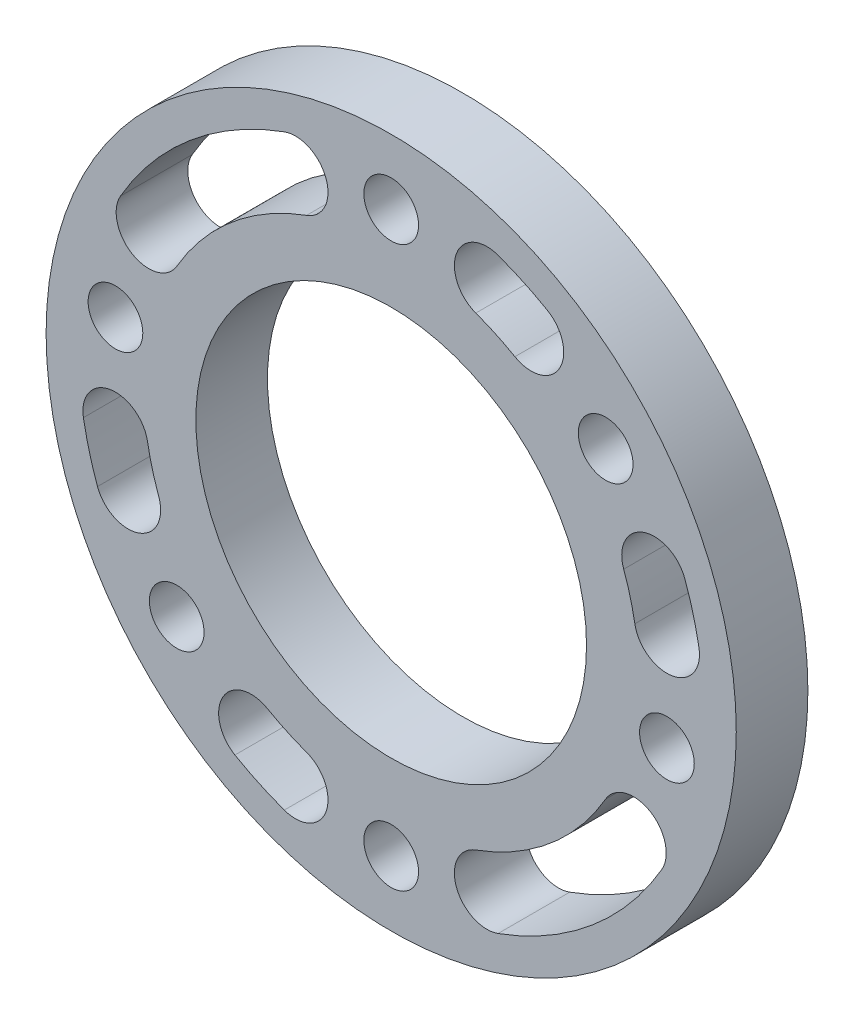
SolidWorks part; units mm, degrees
material "6061 合金"
ref_plane "前视基准面" through (0, 0, 0) normal (0, 0, 1) x (1, 0, 0)
ref_plane "上视基准面" through (0, 0, 0) normal (0, 1, 0) x (1, 0, 0)
ref_plane "右视基准面" through (0, 0, 0) normal (1, 0, 0) x (0, 0, -1)
sketch "草图1" plane through (0, 0, 0) normal (0, 0, 1) x (1, 0, 0)
  circle A0 centre (0, 0) radius 15
  circle A1 centre (0, 0) radius 26.5
  circle A2 centre (0, 0) radius 21.5 construction
  circle A3 centre (0, 21.5) radius 2.1
  circle A4 centre (16.47, 13.8199) radius 2.1
  circle A5 centre (21.1734, -3.7334) radius 2.1
  circle A6 centre (0, -21.5) radius 2.1
  circle A7 centre (-16.47, -13.8199) radius 2.1
  circle A8 centre (-21.1734, 3.7334) radius 2.1
  arc A9 (-18.6195, 10.75) -> (-7.3534, 20.2034) centre (0, 0) cw construction
  arc A10 (-8.2085, 22.5526) -> (-20.7846, 12) centre (0, 0) ccw
  arc A11 (-6.4984, 17.8542) -> (-16.4545, 9.5) centre (0, 0) ccw
  arc A12 (-6.4984, 17.8542) -> (-8.2085, 22.5526) centre (-7.3534, 20.2034) ccw
  arc A13 (-20.7846, 12) -> (-16.4545, 9.5) centre (-18.6195, 10.75) ccw
  arc A14 (7.3534, 20.2034) -> (10.75, 18.6195) centre (0, 0) cw construction
  arc A15 (12, 20.7846) -> (8.2085, 22.5526) centre (0, 0) ccw
  arc A16 (9.5, 16.4545) -> (6.4984, 17.8542) centre (0, 0) ccw
  arc A17 (9.5, 16.4545) -> (12, 20.7846) centre (10.75, 18.6195) ccw
  arc A18 (8.2085, 22.5526) -> (6.4984, 17.8542) centre (7.3534, 20.2034) ccw
  arc A19 (18.7113, 3.2993) -> (17.8542, 6.4984) centre (0, 0) ccw
  arc A20 (18.7113, 3.2993) -> (23.6354, 4.1676) centre (21.1734, 3.7334) ccw
  arc A21 (22.5526, 8.2085) -> (17.8542, 6.4984) centre (20.2034, 7.3534) ccw
  arc A22 (23.6354, 4.1676) -> (22.5526, 8.2085) centre (0, 0) ccw
  arc A23 (20.2034, 7.3534) -> (21.1734, 3.7334) centre (0, 0) cw construction
  arc A24 (6.4984, -17.8542) -> (16.4545, -9.5) centre (0, 0) ccw
  arc A25 (6.4984, -17.8542) -> (8.2085, -22.5526) centre (7.3534, -20.2034) ccw
  arc A26 (20.7846, -12) -> (16.4545, -9.5) centre (18.6195, -10.75) ccw
  arc A27 (8.2085, -22.5526) -> (20.7846, -12) centre (0, 0) ccw
  arc A28 (-9.5, -16.4545) -> (-6.4984, -17.8542) centre (0, 0) ccw
  arc A29 (-9.5, -16.4545) -> (-12, -20.7846) centre (-10.75, -18.6195) ccw
  arc A30 (-8.2085, -22.5526) -> (-6.4984, -17.8542) centre (-7.3534, -20.2034) ccw
  arc A31 (-12, -20.7846) -> (-8.2085, -22.5526) centre (0, 0) ccw
  arc A32 (-23.6354, -4.1676) -> (-22.5526, -8.2085) centre (0, 0) ccw
  arc A33 (-22.5526, -8.2085) -> (-17.8542, -6.4984) centre (-20.2034, -7.3534) ccw
  arc A34 (-18.7113, -3.2993) -> (-17.8542, -6.4984) centre (0, 0) ccw
  arc A35 (-18.7113, -3.2993) -> (-23.6354, -4.1676) centre (-21.1734, -3.7334) ccw
  arc A36 (18.6195, -10.75) -> (7.3534, -20.2034) centre (0, 0) cw construction
  arc A37 (-7.3534, -20.2034) -> (-10.75, -18.6195) centre (0, 0) cw construction
  arc A38 (-20.2034, -7.3534) -> (-21.1734, -3.7334) centre (0, 0) cw construction
  point P9 (-13.8199, 16.47)
  point P27 (9.0863, 19.4856)
  point P36 (20.7674, 5.5646)
  point P44 (13.8199, -16.47)
  point P51 (-9.0863, -19.4856)
  point P58 (-20.7674, -5.5646)
  dimension "D1" = 30
  dimension "D2" = 53
  dimension "D3" = 43
  dimension "D4" = 4.2
  dimension "D8" = 2.5
  dimension "D11" = 20
  dimension "D6" = 50
  dimension "D9" = 20
  dimension "D10" = 20
  dimension "D12" = 20
  dimension "D13" = 2
  dimension "D14" = 20
  dimension "D5" = 3
  dimension "D7" = 2
  dimension "D15" = 2
extrude "凸台-拉伸1" add sketch "草图1" along normal blind 5.5
